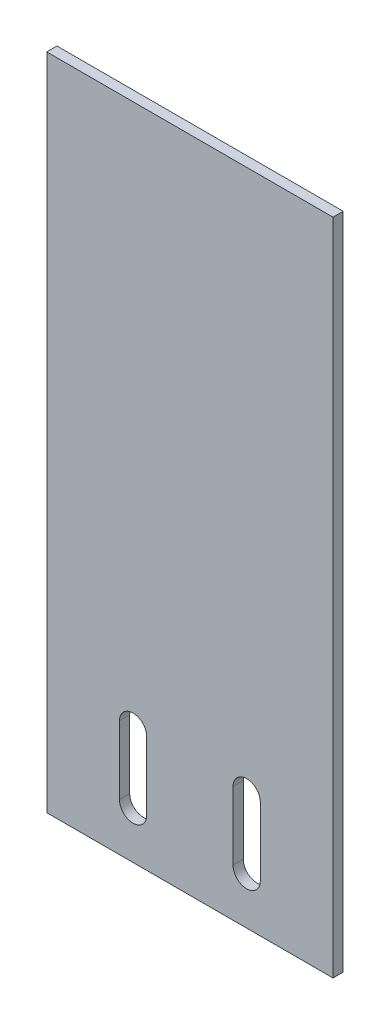
SolidWorks part; units mm, degrees
ref_plane "Front Plane" through (0, 0, 0) normal (0, 0, 1) x (1, 0, 0)
ref_plane "Top Plane" through (0, 0, 0) normal (0, 1, 0) x (1, 0, 0)
ref_plane "Right Plane" through (0, 0, 0) normal (1, 0, 0) x (0, 0, -1)
sketch "Sketch1" plane through (0, 0, 0) normal (0, 0, 1) x (1, 0, 0)
  line L0 (0, 145) -> (0, -145) construction
  line L1 (-63, 145) -> (63, 145)
  line L2 (-63, 145) -> (-63, -145)
  line L3 (-63, -145) -> (63, -145)
  line L4 (63, 145) -> (63, -145)
  line L5 (-63, 145) -> (63, -145) construction
  line L6 (-63, -145) -> (63, 145) construction
  line L7 (-19, 0) -> (-7.6771, 0)
  line L8 (-19, -124) -> (-19, -94)
  line L9 (-19, -94) -> (-25, -94) construction
  line L10 (-31, -94) -> (-31, -124)
  line L11 (19, -124) -> (19, -94)
  line L12 (31, -94) -> (31, -124)
  line L13 (-19, -109) -> (0, -109)
  circle A0 centre (-25, -94) radius 6
  circle A1 centre (-25, -124) radius 6
  circle A2 centre (25, -124) radius 6
  circle A3 centre (25, -94) radius 6
  point P0 (0, 0)
  point P19 (-31, -109)
  point P27 (-31, -124)
  point P28 (-19, -124)
  point P29 (19, -124)
  point P30 (31, -124)
  point P31 (-31, -124)
  point P32 (-19, -124)
  dimension "D3" = 21
  dimension "D6" = 12
  dimension "D1" = 290
  dimension "D2" = 126
  dimension "D4" = 30
  dimension "D5" = 6
  dimension "D7" = 19
  dimension "D8" = 30
extrude "Boss-Extrude2" add sketch "Sketch1" along normal blind 4.5
